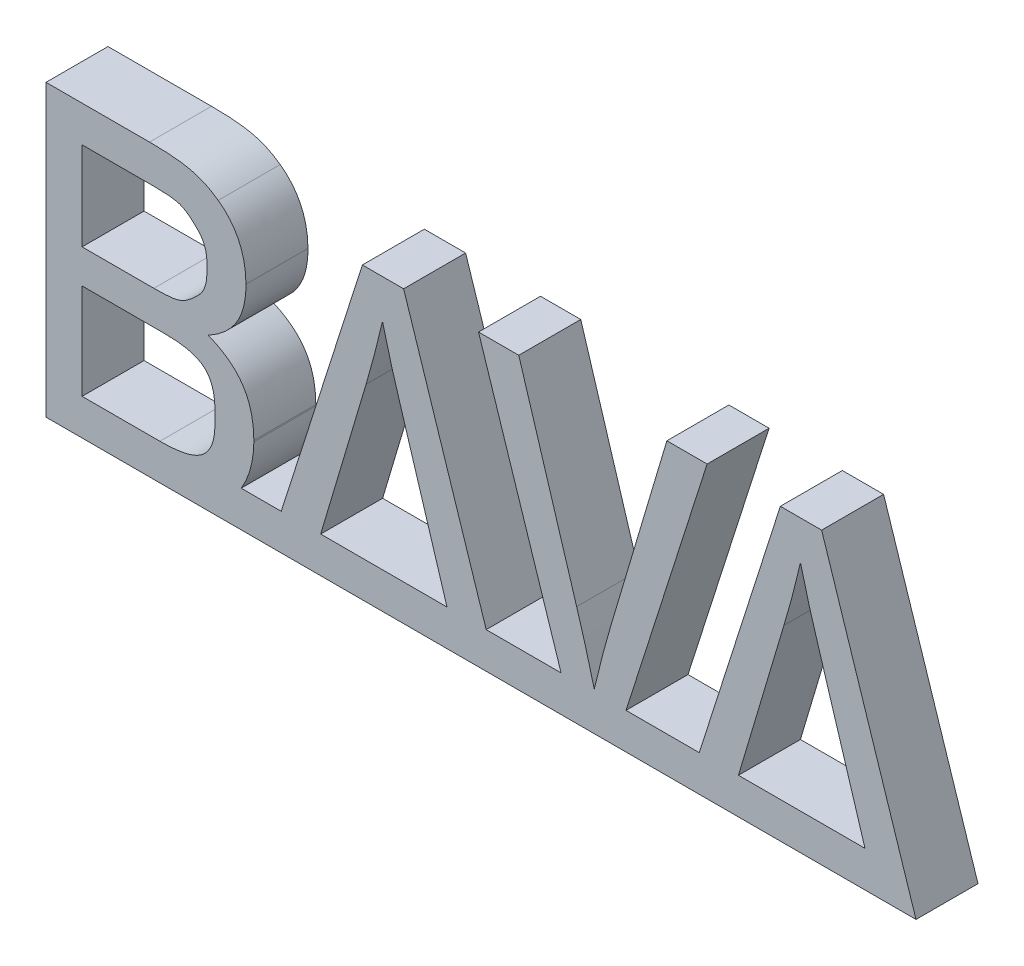
SolidWorks part; units mm, degrees
ref_plane "Front Plane" through (0, 0, 0) normal (0, 0, 1) x (1, 0, 0)
ref_plane "Top Plane" through (0, 0, 0) normal (0, 1, 0) x (1, 0, 0)
ref_plane "Right Plane" through (0, 0, 0) normal (1, 0, 0) x (0, 0, -1)
sketch "Sketch1" plane through (0, 0, 0) normal (0, 0, 1) x (1, 0, 0)
  line L0 (-21.9048, 37.0912) -> (-20.3921, 32.1716)
  line L1 (-20.3921, 32.1716) -> (-24.4751, 32.1716)
  line L2 (-24.4751, 32.1716) -> (-23.0092, 37.0912)
  line L3 (-37.9555, 32.1716) -> (-36.4896, 37.0912)
  line L4 (-35.392, 37.0912) -> (-33.8792, 32.1716)
  line L5 (-33.8792, 32.1716) -> (-37.9555, 32.1716)
  line L6 (-45.6528, 32.1716) -> (-45.6528, 35.2572)
  line L7 (-45.6528, 35.2572) -> (-43.009, 35.2572)
  line L8 (-43.1428, 32.1716) -> (-45.6528, 32.1716)
  line L9 (-45.6528, 39.1996) -> (-43.337, 39.1996)
  line L10 (-43.337, 36.3482) -> (-45.6528, 36.3482)
  line L11 (-45.6528, 36.3482) -> (-45.6528, 39.1996)
  line L12 (-21.7911, 40.3643) -> (-23.123, 40.3643)
  line L13 (-23.123, 40.3643) -> (-25.7401, 32.1716)
  line L14 (-25.7401, 32.1716) -> (-28.1029, 32.1716)
  line L15 (-28.1029, 32.1716) -> (-25.4858, 40.3643)
  line L16 (-25.4858, 40.3643) -> (-26.7843, 40.3643)
  line L17 (-26.7843, 40.3643) -> (-28.5982, 34.2733)
  line L18 (-29.6959, 34.2733) -> (-31.5633, 40.3643)
  line L19 (-31.5633, 40.3643) -> (-32.8618, 40.3643)
  line L20 (-32.8618, 40.3643) -> (-30.1979, 32.1716)
  line L21 (-30.1979, 32.1716) -> (-32.6142, 32.1716)
  line L22 (-32.6142, 32.1716) -> (-35.2781, 40.3643)
  line L23 (-35.2781, 40.3643) -> (-36.6101, 40.3643)
  line L24 (-36.6101, 40.3643) -> (-39.2272, 32.1716)
  line L25 (-39.2272, 32.1716) -> (-40.519, 32.1716)
  line L26 (-43.4775, 40.3643) -> (-46.8175, 40.3643)
  line L27 (-46.8175, 40.3643) -> (-46.8175, 31.0069)
  line L28 (-46.8175, 31.0069) -> (-18.7456, 31.0069)
  line L29 (-18.7456, 31.0069) -> (-21.7911, 40.3643)
  line L30 (-21.9048, 37.0912) -> (-20.3921, 32.1716)
  line L31 (-20.3921, 32.1716) -> (-24.4751, 32.1716)
  line L32 (-24.4751, 32.1716) -> (-23.0092, 37.0912)
  line L33 (-37.9555, 32.1716) -> (-36.4896, 37.0912)
  line L34 (-35.392, 37.0912) -> (-33.8792, 32.1716)
  line L35 (-33.8792, 32.1716) -> (-37.9555, 32.1716)
  line L36 (-45.6528, 32.1716) -> (-45.6528, 35.2572)
  line L37 (-45.6528, 35.2572) -> (-43.009, 35.2572)
  line L38 (-43.1428, 32.1716) -> (-45.6528, 32.1716)
  line L39 (-45.6528, 39.1996) -> (-43.337, 39.1996)
  line L40 (-43.337, 36.3482) -> (-45.6528, 36.3482)
  line L41 (-45.6528, 36.3482) -> (-45.6528, 39.1996)
  line L42 (-21.7911, 40.3643) -> (-23.123, 40.3643)
  line L43 (-23.123, 40.3643) -> (-25.7401, 32.1716)
  line L44 (-25.7401, 32.1716) -> (-28.1029, 32.1716)
  line L45 (-28.1029, 32.1716) -> (-25.4858, 40.3643)
  line L46 (-25.4858, 40.3643) -> (-26.7843, 40.3643)
  line L47 (-26.7843, 40.3643) -> (-28.5982, 34.2733)
  line L48 (-29.6959, 34.2733) -> (-31.5633, 40.3643)
  line L49 (-31.5633, 40.3643) -> (-32.8618, 40.3643)
  line L50 (-32.8618, 40.3643) -> (-30.1979, 32.1716)
  line L51 (-30.1979, 32.1716) -> (-32.6142, 32.1716)
  line L52 (-32.6142, 32.1716) -> (-35.2781, 40.3643)
  line L53 (-35.2781, 40.3643) -> (-36.6101, 40.3643)
  line L54 (-36.6101, 40.3643) -> (-39.2272, 32.1716)
  line L55 (-39.2272, 32.1716) -> (-40.519, 32.1716)
  line L56 (-43.4775, 40.3643) -> (-46.8175, 40.3643)
  line L57 (-46.8175, 40.3643) -> (-46.8175, 31.0069)
  line L58 (-46.8175, 31.0069) -> (-18.7456, 31.0069)
  line L59 (-18.7456, 31.0069) -> (-21.7911, 40.3643)
  spline S0 degree 3 poles (-23.0092, 37.0912) (-22.8084, 37.7672) (-22.6946, 38.1755) (-22.4737, 39.1126) knots 0 0 0 0 1 1 1 1
  spline S1 degree 3 poles (-22.4737, 39.1126) (-22.1926, 38.0483) (-22.1525, 37.881) (-21.9048, 37.0912) knots 1 1 1 1 2 2 2 2
  spline S2 degree 3 poles (-36.4896, 37.0912) (-36.2955, 37.7672) (-36.1818, 38.1755) (-35.9609, 39.1126) knots 1 1 1 1 2 2 2 2
  spline S3 degree 3 poles (-35.9609, 39.1126) (-35.6798, 38.0483) (-35.6396, 37.881) (-35.392, 37.0912) knots 2 2 2 2 3 3 3 3
  spline S4 degree 3 poles (-43.009, 35.2572) (-41.9581, 35.2572) (-41.3624, 34.7084) (-41.3624, 33.7244) knots 2 2 2 2 3 3 3 3
  spline S5 degree 3 poles (-41.3624, 33.7244) (-41.3624, 32.7606) (-42.0385, 32.1716) (-43.1428, 32.1716) knots 3 3 3 3 4 4 4 4
  spline S6 degree 3 poles (-43.337, 39.1996) (-42.7278, 39.1996) (-42.353, 39.0858) (-42.0652, 38.8314) knots 1 1 1 1 2 2 2 2
  spline S7 degree 3 poles (-42.0652, 38.8314) (-41.7908, 38.5838) (-41.6235, 38.1889) (-41.6235, 37.7806) knots 2 2 2 2 3 3 3 3
  spline S8 degree 3 poles (-41.6235, 37.7806) (-41.6235, 37.3589) (-41.7774, 36.9707) (-42.0652, 36.7164) knots 3 3 3 3 4 4 4 4
  spline S9 degree 3 poles (-42.0652, 36.7164) (-42.353, 36.462) (-42.7278, 36.3482) (-43.337, 36.3482) knots 4 4 4 4 5 5 5 5
  spline S10 degree 3 poles (-28.5982, 34.2733) (-28.7923, 33.5972) (-28.9061, 33.1957) (-29.1269, 32.2519) knots 6 6 6 6 7 7 7 7
  spline S11 degree 3 poles (-29.1269, 32.2519) (-29.4148, 33.3161) (-29.4483, 33.4902) (-29.6959, 34.2733) knots 7 7 7 7 8 8 8 8
  spline S12 degree 3 poles (-40.519, 32.1716) (-40.258, 32.5932) (-40.1108, 33.122) (-40.1108, 33.6977) knots 16 16 16 16 17 17 17 17
  spline S13 degree 3 poles (-40.1108, 33.6977) (-40.1108, 34.8221) (-40.5726, 35.5116) (-41.5833, 35.9132) knots 17 17 17 17 18 18 18 18
  spline S14 degree 3 poles (-41.5833, 35.9132) (-40.7399, 36.375) (-40.3651, 37.0109) (-40.3651, 37.9479) knots 18 18 18 18 19 19 19 19
  spline S15 degree 3 poles (-40.3651, 37.9479) (-40.3651, 38.7645) (-40.6797, 39.4339) (-41.262, 39.8422) knots 19 19 19 19 20 20 20 20
  spline S16 degree 3 poles (-41.262, 39.8422) (-41.7908, 40.2371) (-42.353, 40.3643) (-43.4775, 40.3643) knots 20 20 20 20 21 21 21 21
  spline S17 degree 3 poles (-23.0092, 37.0912) (-22.8084, 37.7672) (-22.6946, 38.1755) (-22.4737, 39.1126) (-22.1926, 38.0483) (-22.1525, 37.881) (-21.9048, 37.0912) knots 0 0 0 0 1 2 3 4 4 4 4
  spline S18 degree 3 poles (-36.4896, 37.0912) (-36.2955, 37.7672) (-36.1818, 38.1755) (-35.9609, 39.1126) (-35.6798, 38.0483) (-35.6396, 37.881) (-35.392, 37.0912) knots 0 0 0 0 1 2 3 4 4 4 4
  spline S19 degree 3 poles (-43.009, 35.2572) (-41.9581, 35.2572) (-41.3624, 34.7084) (-41.3624, 33.7244) (-41.3624, 32.7606) (-42.0385, 32.1716) (-43.1428, 32.1716) knots 0 0 0 0 1 2 3 4 4 4 4
  spline S20 degree 3 poles (-43.337, 39.1996) (-42.7278, 39.1996) (-42.353, 39.0858) (-42.0652, 38.8314) (-41.7908, 38.5838) (-41.6235, 38.1889) (-41.6235, 37.7806) (-41.6235, 37.3589) (-41.7774, 36.9707) (-42.0652, 36.7164) (-42.353, 36.462) (-42.7278, 36.3482) (-43.337, 36.3482) knots 0 0 0 0 1 2 3 4 5 6 7 8 9 10 10 10 10
  spline S21 degree 3 poles (-28.5982, 34.2733) (-28.7923, 33.5972) (-28.9061, 33.1957) (-29.1269, 32.2519) (-29.4148, 33.3161) (-29.4483, 33.4902) (-29.6959, 34.2733) knots 0 0 0 0 1 2 3 4 4 4 4
  spline S22 degree 3 poles (-40.519, 32.1716) (-40.258, 32.5932) (-40.1108, 33.122) (-40.1108, 33.6977) (-40.1108, 34.8221) (-40.5726, 35.5116) (-41.5833, 35.9132) (-40.7399, 36.375) (-40.3651, 37.0109) (-40.3651, 37.9479) (-40.3651, 38.7645) (-40.6797, 39.4339) (-41.262, 39.8422) (-41.7908, 40.2371) (-42.353, 40.3643) (-43.4775, 40.3643) knots 0 0 0 0 1 2 3 4 5 6 7 8 9 10 11 12 13 13 13 13
extrude "Boss-Extrude1" add sketch "Sketch1" along normal blind 2 contours S12 S22 S13 S14 S15 S16 L26 L27 L28 L29 L12 L13 L14 L15 L16 L17 S10 S11 L18 L19 L20 L21 L22 L23 L24 L25 S2 S3 L4 L5 L3 S0 S1 L0 L1 L2 L7 S19 L8 L6 L9 S20 S6 S7
